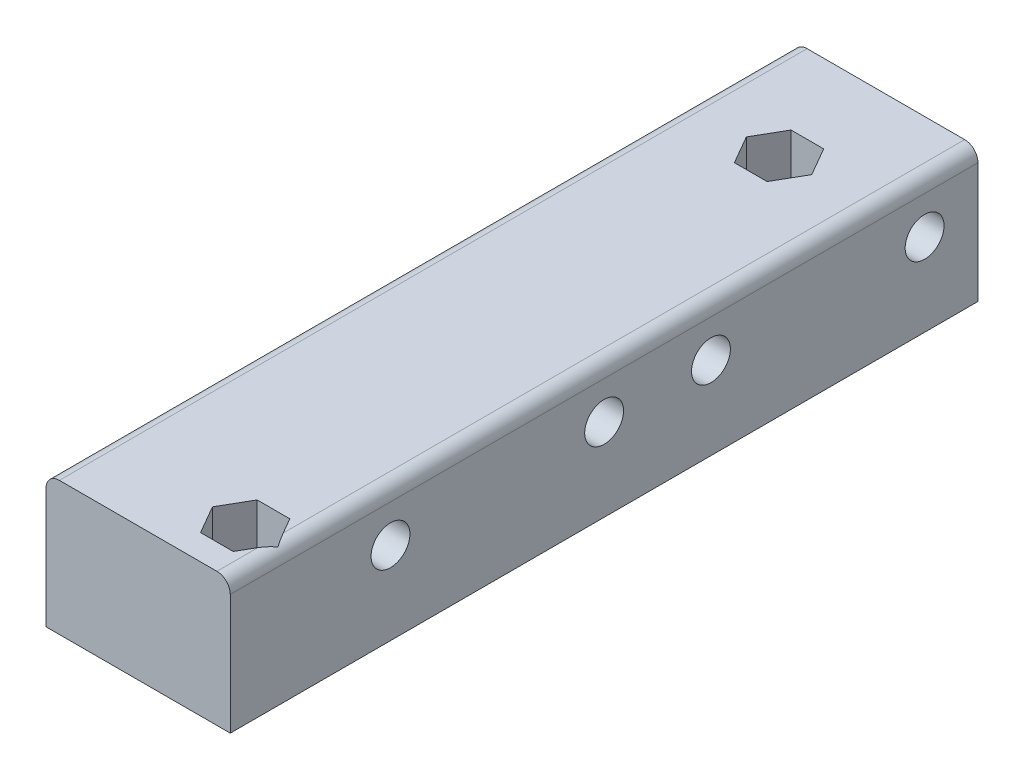
SolidWorks part; units mm, degrees
ref_plane "Front Plane" through (0, 0, 0) normal (0, 0, 1) x (1, 0, 0)
ref_plane "Top Plane" through (0, 0, 0) normal (0, 1, 0) x (1, 0, 0)
ref_plane "Right Plane" through (0, 0, 0) normal (1, 0, 0) x (0, 0, -1)
sketch "Sketch1" plane through (0, 0, 0) normal (0, 0, 1) x (1, 0, 0)
  line L1 (0, 0) -> (21.9075, 0)
  line L2 (0, 0) -> (0, 15.875)
  line L3 (0, 15.875) -> (21.9075, 15.875)
  line L4 (21.9075, 0) -> (21.9075, 15.875)
  dimension "D1" = 21.9075
  dimension "D2" = 15.875
extrude "Boss-Extrude1" add sketch "Sketch1" along normal blind 101.6
fillet "Fillet1" radius 1.5875 2 edges at (21.9075, 15.875, 50.8) (0, 15.875, 50.8)
sketch "Sketch2" plane through (21.9075, 0, 0) normal (1, 0, 0) x (0, 0, -1)
  line L0 (-44.45, 9.8298) -> (-19.05, 9.8298) construction
  circle A0 centre (-57.15, 9.8298) radius 2.3114 construction
  circle A1 centre (-57.15, 9.8298) radius 2.3114
  circle A2 centre (-44.45, 9.8298) radius 2.3114 construction
  circle A3 centre (-44.45, 9.8298) radius 2.3114
  circle A4 centre (-82.55, 9.8298) radius 2.3114 construction
  circle A5 centre (-82.55, 9.8298) radius 2.3114
  circle A6 centre (-6.35, 9.8298) radius 2.3114 construction
  circle A7 centre (-6.35, 9.8298) radius 2.3114
  circle A8 centre (-19.05, 9.8298) radius 2.3114
  dimension "D1" = 25.4
extrude "Cut-Extrude2" cut sketch "Sketch2" against normal up to surface (21.9075 mm away) up to face at (0, 7.1437, 50.8)
sketch "Sketch3" plane through (0, 0, 0) normal (0, -1, 0) x (1, 0, 0)
  line L0 (0, 101.6) -> (21.9075, 101.6) construction
  line L1 (19.2468, 98.5888) -> (15.3607, 98.5888)
  line L2 (15.3607, 98.5888) -> (13.4176, 95.2233)
  line L3 (13.4176, 95.2233) -> (15.3607, 91.8578)
  line L4 (15.3607, 91.8578) -> (19.2468, 91.8578)
  line L5 (19.2468, 91.8578) -> (21.1899, 95.2233)
  line L6 (21.1899, 95.2233) -> (19.2468, 98.5888)
  line L7 (12.8968, 28.7655) -> (9.0107, 28.7655)
  line L8 (9.0107, 28.7655) -> (7.0676, 25.4)
  line L9 (7.0676, 25.4) -> (9.0107, 22.0345)
  line L10 (9.0107, 22.0345) -> (12.8968, 22.0345)
  line L11 (12.8968, 22.0345) -> (14.8399, 25.4)
  line L12 (14.8399, 25.4) -> (12.8968, 28.7655)
  line L13 (21.9075, 101.6) -> (21.9075, 0) construction
  line L14 (0, 101.6) -> (0, 0) construction
  line L15 (0, 0) -> (21.9075, 0) construction
  circle A4 centre (17.3037, 95.2233) radius 3.3655 construction
  circle A5 centre (10.9537, 25.4) radius 3.3655 construction
  dimension "D1" = 6.731
  dimension "D2" = 6.731
  dimension "D3" = 6.3767
  dimension "D4" = 4.6038
  dimension "D5" = 10.9537
  dimension "D6" = 25.4
extrude "Cut-Extrude3" cut sketch "Sketch3" against normal up to next
sketch "Sketch4" plane through (0, 0, 0) normal (0, 0, -1) x (-1, 0, 0)
  line L0 (-20.32, 15.875) -> (-1.5875, 15.875) construction
  line L1 (-21.9075, 0) -> (0, 0)
  line L2 (-21.9075, 0) -> (-21.9075, 15.875)
  line L3 (-21.9075, 15.875) -> (0, 15.875)
  line L4 (0, 0) -> (0, 15.875)
  point P5 (-21.9075, 16.3958)
  dimension "D1" = 15.875
extrude "Cut-Extrude4" cut sketch "Sketch4" against normal blind 12.7
